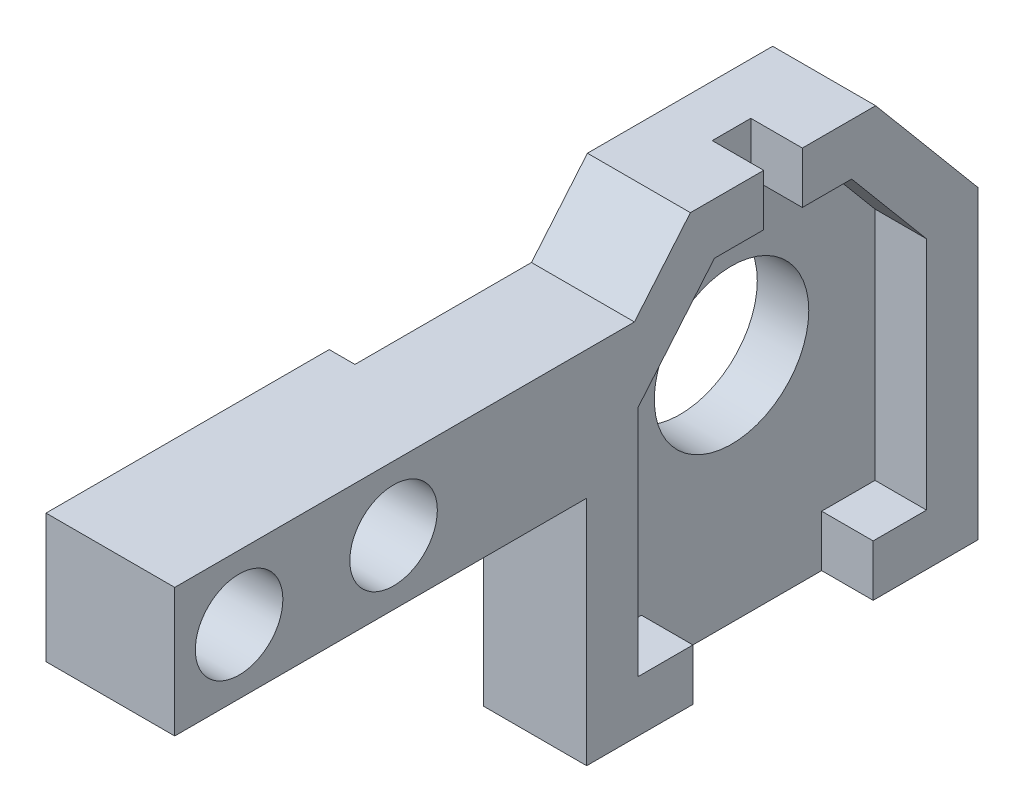
SolidWorks part; units mm, degrees
ref_plane "Front Plane" through (0, 0, 0) normal (0, 0, 1) x (1, 0, 0)
ref_plane "Top Plane" through (0, 0, 0) normal (0, 1, 0) x (1, 0, 0)
ref_plane "Right Plane" through (0, 0, 0) normal (1, 0, 0) x (0, 0, -1)
sketch "Sketch1" plane through (0, 0, 0) normal (1, 0, 0) x (0, 0, -1)
  line L0 (-6.1093, 3.9687) -> (-3.1473, 7.4987)
  line L1 (-3.1473, 7.4987) -> (-1.2321, 7.4987)
  line L2 (-6.1093, 3.9687) -> (-6.1093, -5.0913)
  line L3 (-6.1093, -5.0913) -> (-3.9821, -5.0913)
  line L4 (5.0907, 4.0335) -> (5.0907, -5.0913)
  line L5 (-4.0799, 9.4987) -> (-1.2321, 9.4987)
  line L6 (-8.1093, 4.6966) -> (-8.1093, -7.0913)
  line L7 (-8.1093, -7.0913) -> (-3.9821, -7.0913)
  line L8 (7.0907, 4.7614) -> (7.0907, -7.0913)
  line L9 (5.0907, 4.0335) -> (2.1831, 7.4987)
  line L10 (-8.1093, 4.6966) -> (-4.0799, 9.4987)
  line L11 (3.1157, 9.4987) -> (7.0907, 4.7614)
  line L12 (0.2679, 7.4987) -> (0.2679, 9.4987)
  line L13 (-1.2321, 7.4987) -> (-1.2321, 9.4987)
  line L14 (3.0179, -5.0913) -> (3.0179, -7.0913)
  line L15 (-3.9821, -5.0913) -> (-3.9821, -7.0913)
  line L16 (-0.4821, 1.9087) -> (-0.4821, -6.5913) construction
  line L17 (-8.1093, 1.9087) -> (7.0907, 1.9087) construction
  line L18 (0.2679, 9.4987) -> (3.1157, 9.4987)
  line L19 (0.2679, 7.4987) -> (2.1831, 7.4987)
  line L20 (3.0179, -5.0913) -> (5.0907, -5.0913)
  line L21 (3.0179, -7.0913) -> (7.0907, -7.0913)
  point P20 (1.2255, 7.4987)
  dimension "D1" = 2
  dimension "D2" = 2
  dimension "D3" = 2
  dimension "D4" = 2
  dimension "D5" = 2
  dimension "D6" = 2
  dimension "D7" = 40
  dimension "D8" = 40
  dimension "D9" = 3.53
  dimension "D10" = 3.5
  dimension "D11" = 7
  dimension "D12" = 3.5
  dimension "D13" = 0.75
  dimension "D14" = 0.75
  dimension "D15" = 5.59
  dimension "D16" = 11.2
sketch "Sketch2" plane through (0, 0, 0) normal (1, 0, 0) x (0, 0, -1)
  line L0 (-8.1093, -7.0913) -> (-8.1093, 4.6966)
  line L1 (-8.1093, 4.6966) -> (-4.0799, 9.4987)
  line L2 (-4.0799, 9.4987) -> (3.1157, 9.4987)
  line L3 (3.1157, 9.4987) -> (7.0907, 4.7614)
  line L4 (7.0907, 4.7614) -> (7.0907, -7.0913)
  line L5 (7.0907, -7.0913) -> (-8.1093, -7.0913)
extrude "Boss-Extrude1" add sketch "Sketch2" against normal blind 2
extrude "Boss-Extrude2" add sketch "Sketch1" along normal blind 2
sketch "Sketch3" plane through (0, 0, 0) normal (1, 0, 0) x (0, 0, -1)
  circle A0 centre (-0.4821, 1.9087) radius 3
extrude "Cut-Extrude1" cut sketch "Sketch3" against normal blind 2
sketch "Sketch4" plane through (2, 0, 0) normal (1, 0, 0) x (0, 0, -1)
  line L0 (-15.4821, 1.9087) -> (-8.1093, 1.9087)
  line L7 (-6.2532, 6.9087) -> (-20.486, 6.9087)
  line L19 (-8.1093, 4.6966) -> (-8.1093, 1.9087)
  line L20 (-8.1093, 4.6966) -> (-6.2532, 6.9087)
  line L21 (-4.0799, 9.4987) -> (-8.1093, 4.6966) construction
  line L22 (-15.4821, 1.9087) -> (-24.1093, 1.9087)
  line L23 (-24.1093, 1.9087) -> (-24.1093, 6.9087)
  line L24 (-24.1093, 6.9087) -> (-20.486, 6.9087)
  circle A0 centre (-15.6093, 4.4087) radius 1.7
  circle A2 centre (-21.6093, 4.4087) radius 1.7
  dimension "D7" = 3.4
  dimension "D6" = 3.4
  dimension "D1" = 5
  dimension "D3" = 2.5
  dimension "D4" = 2.5
  dimension "D5" = 6
extrude "Boss-Extrude3" add sketch "Sketch4" against normal blind 5
sketch "Sketch5" plane through (-3, 0, 0) normal (-1, 0, 0) x (0, 0, 1)
  line L7 (6.2532, 6.9087) -> (24.1093, 6.9087) construction
  line L8 (8.1093, 6.9087) -> (6.2532, 6.9087)
  line L9 (6.2532, 6.9087) -> (8.1093, 4.6966)
  line L10 (8.1093, 6.9087) -> (13.1093, 6.9087)
  line L11 (13.1093, 6.9087) -> (13.1093, 1.9087)
  line L12 (24.1093, 1.9087) -> (8.1093, 1.9087) construction
  line L13 (13.1093, 1.9087) -> (8.1093, 1.9087)
  line L14 (8.1093, 1.9087) -> (8.1093, 4.6966)
  circle A0 centre (15.6093, 4.4087) radius 1.7 construction
  dimension "D1" = 2.5
extrude "Cut-Extrude2" cut sketch "Sketch5" against normal blind 1
